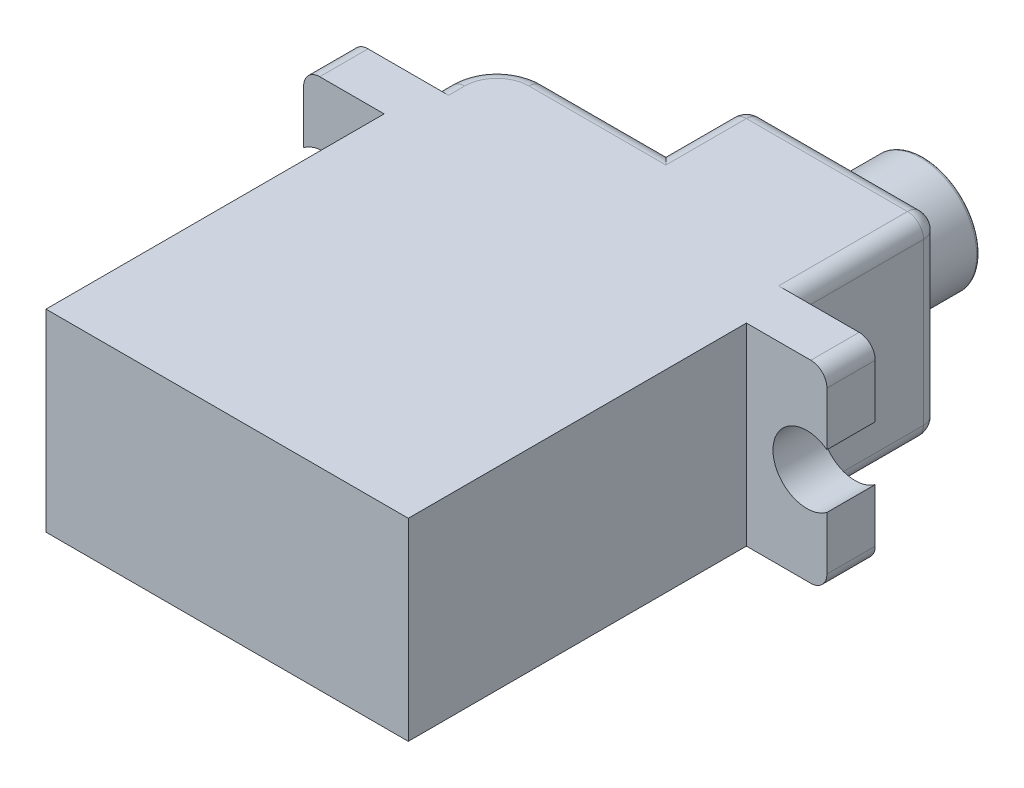
SolidWorks part; units mm, degrees
ref_plane "Front Plane" through (0, 0, 0) normal (0, 0, 1) x (1, 0, 0)
ref_plane "Top Plane" through (0, 0, 0) normal (0, 1, 0) x (1, 0, 0)
ref_plane "Right Plane" through (0, 0, 0) normal (1, 0, 0) x (0, 0, -1)
sketch "Sketch1" plane through (0, 0, 0) normal (0, 0, 1) x (1, 0, 0)
  line L1 (-11.25, -6) -> (11.25, -6)
  line L2 (-11.25, -6) -> (-11.25, 6)
  line L3 (-11.25, 6) -> (11.25, 6)
  line L4 (11.25, -6) -> (11.25, 6)
  line L5 (-11.25, -6) -> (11.25, 6) construction
  line L6 (-11.25, 6) -> (11.25, -6) construction
  point P0 (0, 0)
  dimension "D1" = 22.5
  dimension "D2" = 12
extrude "Boss-Extrude1" add sketch "Sketch1" along normal blind 21
sketch "Sketch2" plane through (0, 0, 0) normal (0, 0, 1) x (1, 0, 0)
  line L1 (16.25, -6) -> (-16.25, -6)
  line L2 (16.25, -6) -> (16.25, 6)
  line L3 (16.25, 6) -> (-16.25, 6)
  line L4 (-16.25, -6) -> (-16.25, 6)
  line L5 (16.25, -6) -> (-16.25, 6) construction
  line L6 (16.25, 6) -> (-16.25, -6) construction
  point P1 (0, 0)
  dimension "D1" = 32.5
  dimension "D2" = 12
extrude "Boss-Extrude2" add sketch "Sketch2" against normal blind 3 contours L4 L3 L2 L1
sketch "Sketch3" plane through (0, 0, -3) normal (0, 0, -1) x (-1, 0, 0)
  line L1 (-11.25, -6) -> (11.25, -6)
  line L2 (-11.25, -6) -> (-11.25, 6)
  line L3 (-11.25, 6) -> (11.25, 6)
  line L4 (11.25, -6) -> (11.25, 6)
  line L5 (-11.25, -6) -> (11.25, 6) construction
  line L6 (-11.25, 6) -> (11.25, -6) construction
  point P0 (0, 0)
  dimension "D1" = 22.5
  dimension "D2" = 12
extrude "Boss-Extrude6" add sketch "Sketch3" along normal blind 4 contours L2 L3 L4 L1
sketch "Sketch5" plane through (0, 0, -7) normal (0, 0, -1) x (-1, 0, 0)
  line L0 (-11.25, -6) -> (11.25, -6) construction
  line L1 (-11.25, 6) -> (0.75, 6)
  line L2 (-11.25, 6) -> (-11.25, -6)
  line L3 (-11.25, -6) -> (0.75, -6)
  line L4 (0.75, 6) -> (0.75, -6)
  dimension "D1" = 12
extrude "Boss-Extrude7" add sketch "Sketch5" along normal blind 5 contours L4 L3 L2 L1
sketch "Sketch6" plane through (0, 0, -12) normal (0, 0, -1) x (-1, 0, 0)
  line L0 (-11.25, 6) -> (0.75, -6) construction
  circle A0 centre (-5.25, 0) radius 3.5
  dimension "D1" = 7
extrude "Boss-Extrude8" add sketch "Sketch6" along normal blind 5 contours A0
sketch "Sketch7" plane through (0, 0, -17) normal (0, 0, -1) x (-1, 0, 0)
  circle A0 centre (-5.25, 0) radius 1.2
  dimension "D1" = 2.4
extrude "Cut-Extrude1" cut sketch "Sketch7" against normal blind 5 contours A0
fillet "Fillet3" radius 3 1 edges at (-11.25, 0, -7)
fillet "Fillet4" radius 1 1 edges at (11.25, 0, -12)
fillet "Fillet5" radius 1 1 edges at (-0.75, 0, -12)
fillet "Fillet6" radius 1 5 edges at (10.9571, -6, -11.7071) (-0.4571, -6, -11.7071) (5.25, -6, -12)
fillet "Fillet7" radius 1 5 edges at (10.9571, 6, -11.7071) (-0.4571, 6, -11.7071) (5.25, 6, -12)
fillet "Fillet8" radius 1 3 edges at (-10.3713, 6, -6.1213)
fillet "Fillet9" radius 1 3 edges at (-10.3713, -6, -6.1213)
fillet "Fillet10" radius 0.2 1 edges at (1.75, 0, -17)
sketch "Sketch9" plane through (0, 0, -3) normal (0, 0, -1) x (-1, 0, 0)
  line L0 (-11.25, -5) -> (-11.25, 5) construction
  line L1 (-16.25, -6) -> (-16.25, 6) construction
  line L3 (-11.25, 0) -> (-16.25, 0) construction
sketch "Sketch13" plane through (0, 0, -3) normal (0, 0, -1) x (-1, 0, 0)
  line L0 (-16.25, 0) -> (-13.75, 0) construction
  line L1 (-11.25, 0) -> (-16.25, 0) construction
  circle A0 centre (-15, 0) radius 2.1
  dimension "D1" = 4.2
sketch "Sketch14" plane through (0, 0, -3) normal (0, 0, -1) x (-1, 0, 0)
  line L1 (16.25, -6) -> (16.25, 6) construction
  line L4 (13.75, 0) -> (16.25, 0) construction
  circle A0 centre (15, 0) radius 2.1
  dimension "D1" = 4.2
extrude "Cut-Extrude4" cut sketch "Sketch14" against normal blind 5 contours A0
extrude "Cut-Extrude5" cut sketch "Sketch13" against normal blind 5 contours A0
fillet "Fillet11" radius 1 4 edges at (-16.25, -6, -1.5) (-16.25, 6, -1.5) (16.25, -6, -1.5) (16.25, 6, -1.5)
